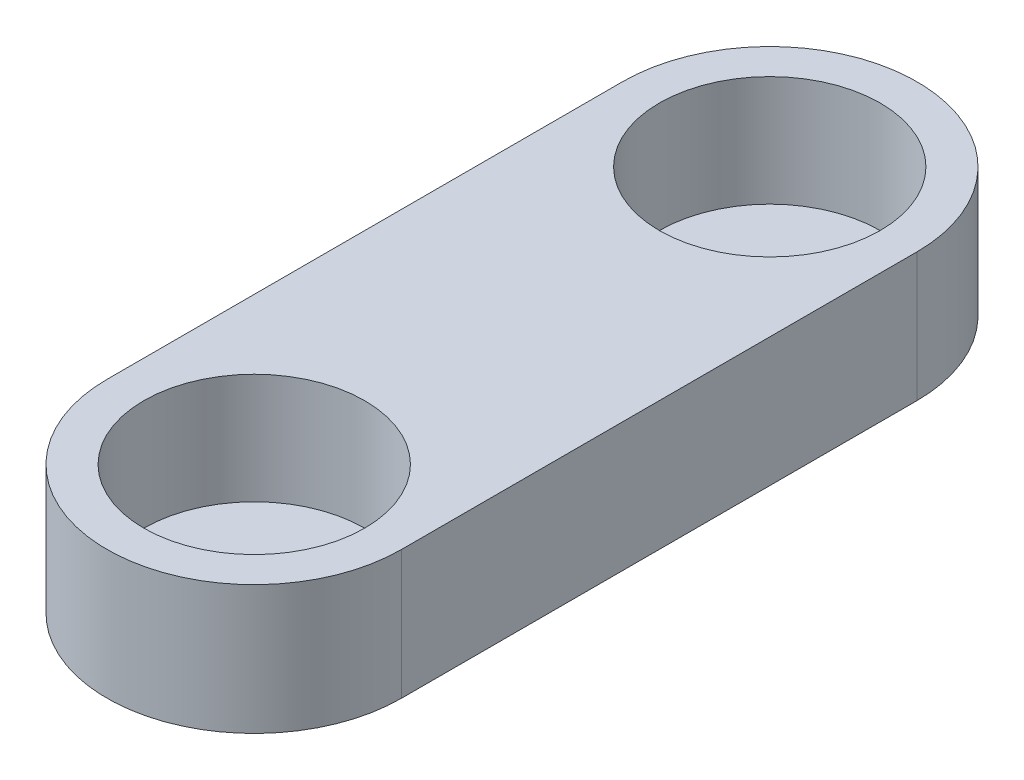
SolidWorks part; units mm, degrees
ref_plane "Front Plane" through (0, 0, 0) normal (0, 0, 1) x (1, 0, 0)
ref_plane "Top Plane" through (0, 0, 0) normal (0, 1, 0) x (1, 0, 0)
ref_plane "Right Plane" through (0, 0, 0) normal (1, 0, 0) x (0, 0, -1)
sketch "Sketch1" plane through (0, 0, 0) normal (0, 1, 0) x (1, 0, 0)
  line L0 (0, 7) -> (0, -7) construction
  line L1 (4, 7) -> (4, -7)
  line L2 (-4, 7) -> (-4, -7)
  arc A1 (4, 7) -> (-4, 7) centre (0, 7) ccw
  arc A2 (-4, -7) -> (4, -7) centre (0, -7) ccw
  circle A3 centre (0, 7) radius 3
  circle A4 centre (0, -7) radius 3
  point P0 (0, -4.9107)
  point P5 (0, 0)
  point P14 (0, 8.4541)
  point P15 (0, -6.604)
  point P16 (0, 0)
  point P17 (4.1902, -6.5055)
  point P18 (0, 0)
  point P19 (0, 0)
  point P20 (0, 7)
  dimension "D2" = 6
  dimension "D3" = 4
  dimension "D4" = 14
extrude "Boss-Extrude1" add sketch "Sketch1" along normal blind 3
sketch "Sketch2" plane through (0, 0, 0) normal (0, -1, 0) x (1, 0, 0)
  line L0 (0, 7) -> (0, -7) construction
  line L1 (4, 7) -> (4, -7)
  line L2 (-4, 7) -> (-4, -7)
  arc A0 (4, 7) -> (-4, 7) centre (0, 7) ccw
  arc A1 (-4, -7) -> (4, -7) centre (0, -7) ccw
  point P4 (0, 0)
  point P9 (0, 0)
extrude "Boss-Extrude2" add sketch "Sketch2" along normal blind 0.5
sketch "Sketch3" plane through (0, -0.5, 0) normal (0, -1, 0) x (1, 0, 0)
  circle A0 centre (0, 0) radius 0.75
  dimension "D1" = 1.5
extrude "Cut-Extrude1" cut sketch "Sketch3" against normal blind 2.5
